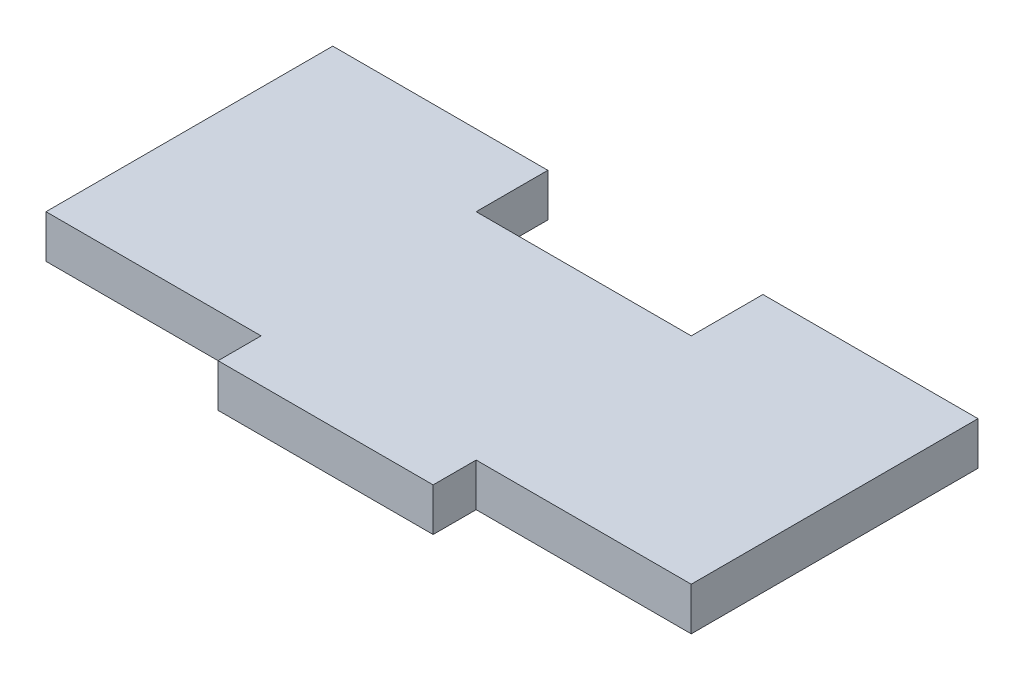
SolidWorks part; units mm, degrees
ref_plane "Front Plane" through (0, 0, 0) normal (0, 0, 1) x (1, 0, 0)
ref_plane "Top Plane" through (0, 0, 0) normal (0, 1, 0) x (1, 0, 0)
ref_plane "Right Plane" through (0, 0, 0) normal (1, 0, 0) x (0, 0, -1)
sketch "Sketch2" plane through (0, 0, 0) normal (0, 1, 0) x (1, 0, 0)
  line L1 (-22.5, -11.5) -> (22.5, -11.5)
  line L2 (-22.5, -11.5) -> (-22.5, 11.5)
  line L3 (-22.5, 11.5) -> (22.5, 11.5)
  line L4 (22.5, -11.5) -> (22.5, 11.5)
  line L5 (-22.5, -11.5) -> (22.5, 11.5) construction
  line L6 (-22.5, 11.5) -> (22.5, -11.5) construction
  point P0 (0, 0)
  dimension "D1" = 45
  dimension "D2" = 23
extrude "Boss-Extrude1" add sketch "Sketch2" along normal blind 3
sketch "Sketch3" plane through (0, 3, 0) normal (0, 1, 0) x (1, 0, 0)
  line L0 (22.5, 11.5) -> (-22.5, 11.5) construction
  line L1 (-7.5, 11.5) -> (7.5, 11.5)
  line L2 (-7.5, 11.5) -> (-7.5, 6.5)
  line L3 (-7.5, 6.5) -> (7.5, 6.5)
  line L4 (7.5, 11.5) -> (7.5, 6.5)
  line L5 (-22.5, 11.5) -> (-22.5, -11.5) construction
  point P6 (-7.5, 9)
  dimension "D1" = 15
  dimension "D2" = 5
  dimension "D3" = 15
extrude "cut for pins" cut sketch "Sketch3" against normal blind 3
sketch "Sketch6" plane through (0, 3, 0) normal (0, 1, 0) x (1, 0, 0)
  line L1 (-22.5, -11.5) -> (-7.5, -11.5)
  line L2 (-22.5, -11.5) -> (-22.5, -8.5)
  line L3 (-22.5, -8.5) -> (-7.5, -8.5)
  line L4 (-7.5, -11.5) -> (-7.5, -8.5)
  line L5 (22.5, -11.5) -> (7.5, -11.5)
  line L6 (22.5, -11.5) -> (22.5, -8.5)
  line L7 (22.5, -8.5) -> (7.5, -8.5)
  line L8 (7.5, -11.5) -> (7.5, -8.5)
  dimension "D1" = 15
  dimension "D2" = 3
  dimension "D3" = 15
  dimension "D4" = 3
extrude "Cut-Extrude3" cut sketch "Sketch6" against normal blind 3
